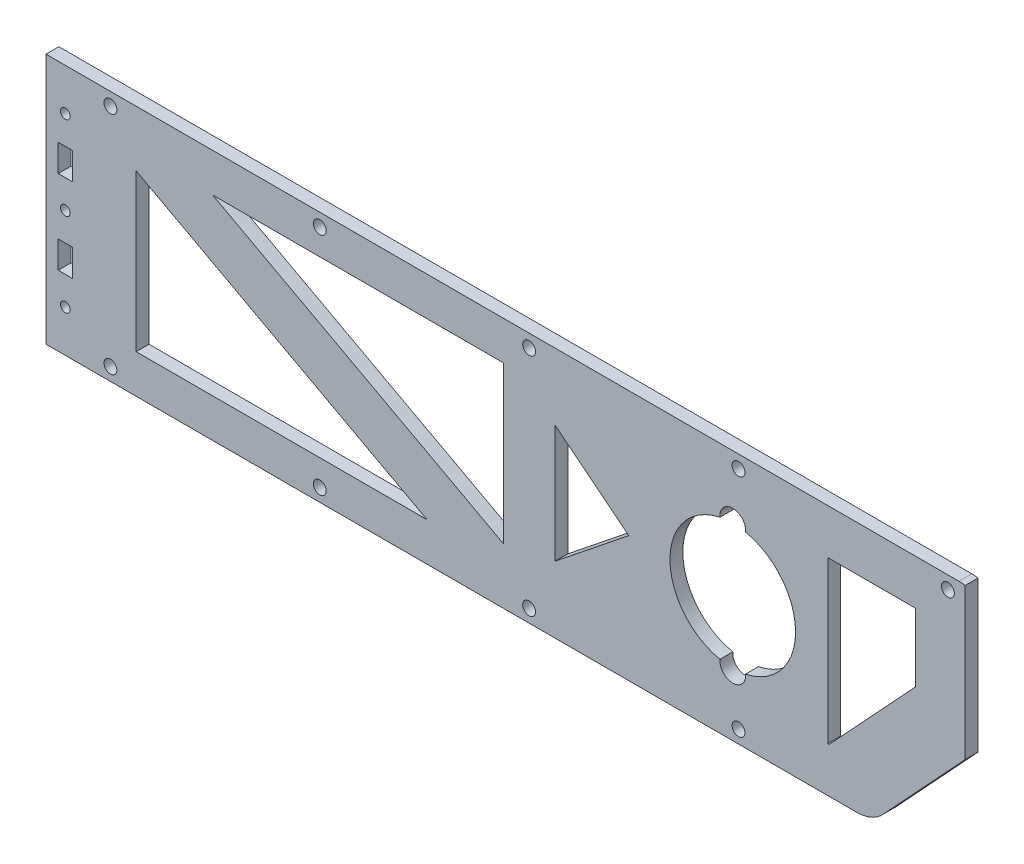
SolidWorks part; units mm, degrees
ref_plane "前视基准面" through (0, 0, 0) normal (0, 0, 1) x (1, 0, 0)
ref_plane "上视基准面" through (0, 0, 0) normal (0, 1, 0) x (1, 0, 0)
ref_plane "右视基准面" through (0, 0, 0) normal (1, 0, 0) x (0, 0, -1)
sketch "草图1" plane through (0, 0, 0) normal (0, 0, 1) x (1, 0, 0)
  line L0 (0, 0) -> (0, 13) construction
  line L1 (0, 13) -> (-8.8556, 13) construction
  line L2 (-2.2, 17.2) -> (2.2, 17.2)
  line L3 (-2.2, 17.2) -> (-2.2, 8.8)
  line L4 (-2.2, 8.8) -> (2.2, 8.8)
  line L5 (2.2, 17.2) -> (2.2, 8.8)
  line L6 (-2.2, 17.2) -> (2.2, 8.8) construction
  line L7 (-2.2, 8.8) -> (2.2, 17.2) construction
  line L8 (0, 26) -> (7.7263, 26) construction
  line L13 (0, 0) -> (-13.815, 0) construction
  line L14 (-2.2, -8.8) -> (2.2, -17.2) construction
  line L15 (-2.2, -17.2) -> (2.2, -8.8) construction
  line L16 (0, -13) -> (-8.8556, -13) construction
  line L17 (2.2, -17.2) -> (2.2, -8.8)
  line L18 (-2.2, -8.8) -> (2.2, -8.8)
  line L19 (-2.2, -17.2) -> (-2.2, -8.8)
  line L20 (-2.2, -17.2) -> (2.2, -17.2)
  line L21 (14, 35) -> (144, 35) construction
  line L22 (-6, 39) -> (294, 39) construction
  line L23 (-6, 39) -> (-6, -39)
  line L24 (-6, -39) -> (294, -39) construction
  line L25 (294, 39) -> (294, -39) construction
  line L26 (144, 35) -> (144, -35) construction
  line L27 (144, -35) -> (14, 35) construction
  line L28 (144, -35) -> (14, -35) construction
  line L29 (14, -35) -> (14, 35) construction
  line L30 (112.2688, -27) -> (22, -27)
  line L31 (22, -27) -> (22, 21.6063)
  line L32 (112.2688, -27) -> (22, 21.6063)
  line L33 (45.7312, 27) -> (136, 27)
  line L34 (136, 27) -> (136, -21.6063)
  line L35 (136, -21.6063) -> (45.7312, 27)
  line L40 (144, 35) -> (209, 35) construction
  line L41 (274, 35) -> (209, 35) construction
  line L45 (187.71, 0) -> (144, 35) construction
  line L46 (144, -35) -> (187.71, 0) construction
  line L47 (152, 18.3455) -> (152, -18.3455)
  line L48 (152, -18.3455) -> (174.9109, 0)
  line L49 (174.9109, 0) -> (152, 18.3455)
  line L55 (236.71, -25) -> (236.71, 25)
  line L56 (236.71, 25) -> (264, 25)
  line L57 (264, 25) -> (264, 3.9269)
  line L58 (237.1393, -25) -> (264, 3.9269)
  line L59 (237.1393, -25) -> (236.71, -25)
  line L60 (253.8336, -35.485) -> (285.491, -1.3924)
  line L61 (288.4302, 6.0925) -> (288.4302, 28)
  line L62 (-6, 39) -> (277.4302, 39)
  line L63 (245.7729, -39) -> (-6, -39)
  circle A0 centre (0, 0) radius 1.5
  circle A1 centre (0, 26) radius 1.5
  circle A2 centre (0, -26) radius 1.5
  circle A9 centre (207.21, 0) radius 19.5 construction
  circle A10 centre (207.21, 19.5) radius 4 construction
  circle A11 centre (207.21, -19.5) radius 4 construction
  arc A12 (203.2311, 19.0897) -> (203.2311, -19.0897) centre (207.21, 0) ccw
  arc A13 (211.1889, 19.0897) -> (211.1889, -19.0897) centre (207.21, 0) cw
  arc A14 (203.2311, -19.0897) -> (211.1889, -19.0897) centre (207.21, -19.5) ccw
  arc A15 (203.2311, 19.0897) -> (211.1889, 19.0897) centre (207.21, 19.5) cw
  circle A16 centre (274, 35) radius 2
  circle A17 centre (209, 35) radius 2
  circle A18 centre (144, 35) radius 2
  circle A19 centre (79, 35) radius 2
  circle A20 centre (14, 35) radius 2
  circle A21 centre (209, -35) radius 2
  circle A22 centre (144, -35) radius 2
  circle A23 centre (79, -35) radius 2
  circle A24 centre (14, -35) radius 2
  circle A25 centre (274, -35) radius 2 construction
  arc A26 (245.7729, -39) -> (253.8336, -35.485) centre (245.7729, -28) ccw
  arc A27 (285.491, -1.3924) -> (288.4302, 6.0925) centre (277.4302, 6.0925) ccw
  arc A28 (288.4302, 28) -> (277.4302, 39) centre (277.4302, 28) ccw
  point P25 (-6, 0)
  point P80 (250.5697, -39)
  point P85 (288.4302, 39)
  dimension "D1" = 3
  dimension "D8" = 207.21
  dimension "D10" = 4
  dimension "D14" = 39
  dimension "D9" = 20
  dimension "D16" = 11
  dimension "D2" = 13
  dimension "D3" = 4.4
  dimension "D4" = 8.4
  dimension "D5" = 78
  dimension "D6" = 300
  dimension "D7" = 6
  dimension "D12" = 2
  dimension "D13" = 8
  dimension "D15" = 8
  dimension "D17" = 8
  dimension "D11" = 5
extrude "凸台-拉伸1" add sketch "草图1" along normal blind 4
sketch "草图2" plane through (0, 0, 4) normal (0, 0, 1) x (1, 0, 0)
  line L0 (279.3498, 38.8312) -> (279.3498, -8.006)
  line L1 (253.8336, -35.485) -> (285.491, -1.3924) construction
  line L2 (279.3498, -8.006) -> (315.853, -9.1398)
  line L3 (315.853, -9.1398) -> (310.0302, 44.3025)
  line L4 (310.0302, 44.3025) -> (279.3498, 38.8312)
  arc A0 (288.4302, 28) -> (277.4302, 39) centre (277.4302, 28) ccw construction
extrude "切除-拉伸1" cut sketch "草图2" against normal blind 10
